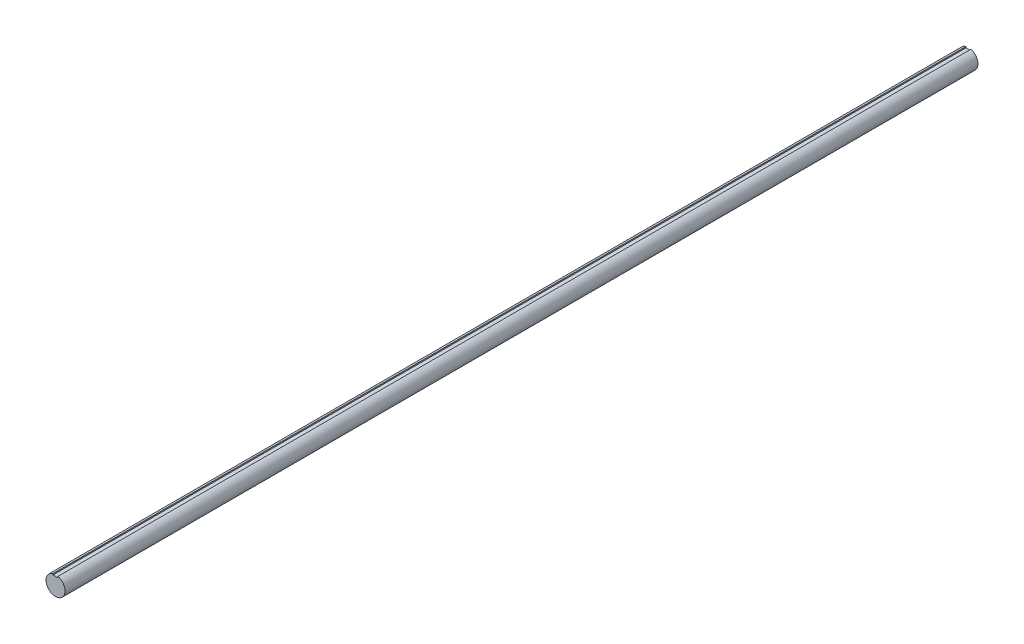
SolidWorks part; units mm, degrees
ref_plane "Front Plane" through (0, 0, 0) normal (0, 0, 1) x (1, 0, 0)
ref_plane "Top Plane" through (0, 0, 0) normal (0, 1, 0) x (1, 0, 0)
ref_plane "Right Plane" through (0, 0, 0) normal (1, 0, 0) x (0, 0, -1)
sketch "Sketch1" plane through (0, 0, 0) normal (0, 0, 1) x (1, 0, 0)
  line L2 (-1.2192, 4.6038) -> (-1.2192, 3.9933)
  line L3 (-1.2192, 3.9933) -> (1.2192, 3.9933)
  line L4 (1.2192, 4.6038) -> (1.2192, 3.9933)
  arc A0 (-1.2192, 4.6038) -> (1.2192, 4.6038) centre (0, 0) ccw
  point P3 (0, 4.7625)
  dimension "D1" = 9.525
extrude "Boss-Extrude1" add sketch "Sketch1" along normal blind 457.2
